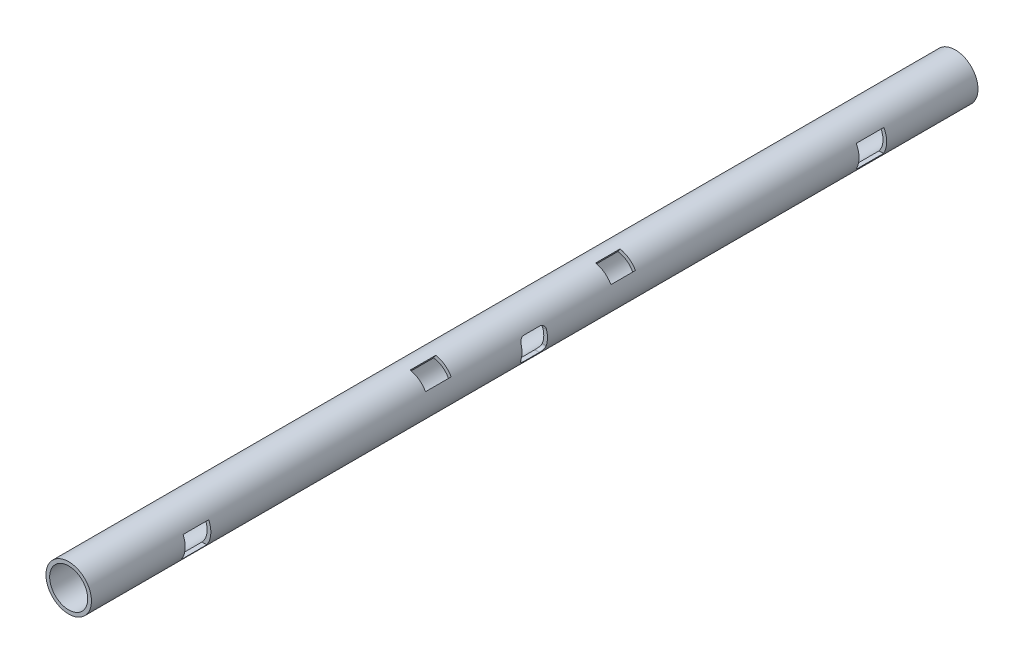
SolidWorks part; units mm, degrees
ref_plane "Front Plane" through (0, 0, 0) normal (0, 0, 1) x (1, 0, 0)
ref_plane "Top Plane" through (0, 0, 0) normal (0, 1, 0) x (1, 0, 0)
ref_plane "Right Plane" through (0, 0, 0) normal (1, 0, 0) x (0, 0, -1)
sketch "Sketch1" plane through (0, 0, 0) normal (0, 0, 1) x (1, 0, 0)
  circle A0 centre (0, 0) radius 25.4
  circle A1 centre (0, 0) radius 21.2611
extrude "Boss-Extrude1" add sketch "Sketch1" along normal blind 990.6
sketch "Sketch2" plane through (0, 0, 0) normal (1, 0, 0) x (0, 0, -1)
  line L0 (-990.6, 0) -> (0, 0) construction
  line L1 (-990.6, 25.4) -> (-990.6, -25.4) construction
  line L2 (-495.3, 0) -> (-495.3, 63.0654) construction
  line L3 (-495.3, 63.0654) -> (-596.9, 63.0654) construction
  line L4 (-495.3, 63.0654) -> (-393.7, 63.0654) construction
  line L6 (-885.7883, 10.7699) -> (-857.1635, 10.7699)
  line L7 (-885.7883, 10.7699) -> (-885.7883, -14.6051)
  line L8 (-885.7883, -14.6051) -> (-857.1635, -14.6051)
  line L9 (-857.1635, 10.7699) -> (-857.1635, -14.6051)
  line L10 (-132.8969, 12.3631) -> (-102.0055, 12.3631)
  line L11 (-132.8969, 12.3631) -> (-132.8969, -13.0119)
  line L12 (-132.8969, -13.0119) -> (-102.0055, -13.0119)
  line L13 (-102.0055, 12.3631) -> (-102.0055, -13.0119)
ref_plane "Plane1" through (54.6962, 0, 0) normal (1, 0, 0) x (0, 0, -1)
extrude "Cut-Extrude1" cut sketch "Sketch2" along normal blind 134.112
sketch "Sketch3" plane through (0, 0, 990.6) normal (0, 0, 1) x (1, 0, 0)
  line L0 (0, 0) -> (20.3428, 31.3251)
  line L1 (0, 0) -> (28.194, 0)
  dimension "D1" = 57
ref_plane "Plane2" through (20.3428, 31.3251, 990.6) normal (0.5446, 0.8387, 0) x (0.8387, -0.5446, 0)
sketch "Sketch4" plane through (20.3428, 31.3251, 990.6) normal (0.5446, 0.8387, 0) x (0.8387, -0.5446, 0)
  line L0 (0, 0) -> (0, 990.6) construction
  line L1 (-25.4, 0) -> (25.4, 0) construction
  line L2 (0, 495.3) -> (-50.8432, 495.3) construction
  line L3 (-50.8432, 495.3) -> (-50.8432, 596.9) construction
  line L4 (-50.8432, 495.3) -> (-50.8432, 393.7) construction
  line L6 (-9.4664, 376.6825) -> (11.6448, 376.6825)
  line L7 (-9.4664, 376.6825) -> (-9.4664, 405.3334)
  line L8 (-9.4664, 405.3334) -> (11.6448, 405.3334)
  line L9 (11.6448, 376.6825) -> (11.6448, 405.3334)
  line L10 (-9.4664, 583.8186) -> (11.6448, 583.8186)
  line L11 (-9.4664, 583.8186) -> (-9.4664, 611.167)
  line L12 (-9.4664, 611.167) -> (11.6448, 611.167)
  line L13 (11.6448, 583.8186) -> (11.6448, 611.167)
extrude "Cut-Extrude3" cut sketch "Sketch4" against normal blind 26.416
sketch "Sketch5" plane through (54.6962, 0, 0) normal (1, 0, 0) x (0, 0, -1)
  line L0 (-990.6, 0) -> (0, 0) construction
  line L1 (-990.6, 0) -> (-990.6, 31.3251) construction
  line L3 (-504.38, 12.4124) -> (-486.1131, 12.4124)
  line L4 (-509.46, 7.3324) -> (-509.46, -8.5959)
  line L5 (-504.38, -13.6759) -> (-486.1131, -13.6759)
  line L6 (-481.0331, 7.3324) -> (-481.0331, -8.5959)
  arc A0 (-504.38, -13.6759) -> (-509.46, -8.5959) centre (-504.38, -8.5959) cw
  arc A1 (-486.1131, -13.6759) -> (-481.0331, -8.5959) centre (-486.1131, -8.5959) ccw
  arc A2 (-481.0331, 7.3324) -> (-486.1131, 12.4124) centre (-486.1131, 7.3324) ccw
  arc A3 (-509.46, 7.3324) -> (-504.38, 12.4124) centre (-504.38, 7.3324) cw
  dimension "D1" = 5.08
extrude "Cut-Extrude4" cut sketch "Sketch5" against normal blind 54.864
